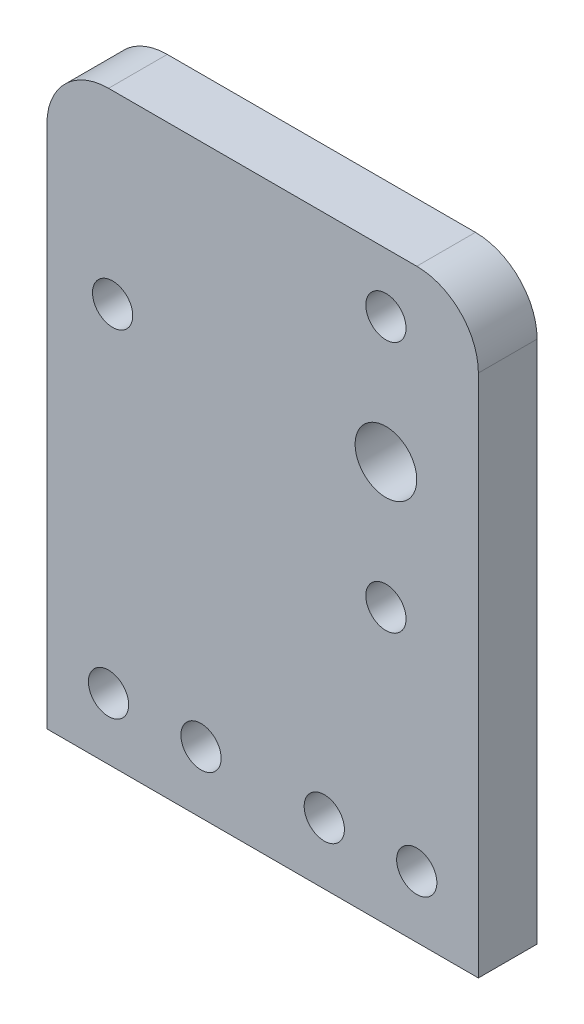
SolidWorks part; units mm, degrees
ref_plane "Front Plane" through (0, 0, 0) normal (0, 0, 1) x (1, 0, 0)
ref_plane "Top Plane" through (0, 0, 0) normal (0, 1, 0) x (1, 0, 0)
ref_plane "Right Plane" through (0, 0, 0) normal (1, 0, 0) x (0, 0, -1)
sketch "Sketch1" plane through (0, 0, 0) normal (0, 0, 1) x (1, 0, 0)
  line L1 (-17.5, 23.75) -> (17.5, 23.75)
  line L2 (-17.5, 23.75) -> (-17.5, -23.75)
  line L3 (-17.5, -23.75) -> (17.5, -23.75)
  line L4 (17.5, 23.75) -> (17.5, -23.75)
  line L5 (-17.5, 23.75) -> (17.5, -23.75) construction
  line L6 (-17.5, -23.75) -> (17.5, 23.75) construction
  circle A0 centre (10, 8.75) radius 2.5
  point P0 (0, 0)
  dimension "D3" = 5
  dimension "D1" = 35
  dimension "D2" = 47.5
  dimension "D4" = 27.5
  dimension "D5" = 32.5
extrude "Boss-Extrude1" add sketch "Sketch1" along normal blind 4.7625
hole_wizard "#4 Clearance Hole1" positions "Sketch2" profile "Sketch3" hole size "#4" standard "ANSI Inch" end condition up to next
sketch "Sketch2" plane through (0, 0, 4.7625) normal (0, 0, 1) x (1, 0, 0)
  circle A1 centre (10, 8.75) radius 2.5 construction
  circle A2 centre (1.28, 8.75) radius 17.57 construction
  point P0 (10, 18.96)
  point P2 (10, -1.46)
  point P4 (-12.17, 8.75)
  dimension "D1" = 35.14
  dimension "D4" = 10.21
  dimension "D5" = 10.21
  dimension "D6" = 22.17
  dimension "D7" = 10.21
  dimension "D2" = 8.72
  dimension "D3" = 8.72
sketch "Sketch3" plane through (10, 18.96, 4.7625) normal (1, 0, 0) x (0, -1, 0)
  line L0 (0, 0) -> (0, 4.7625)
  line L1 (0, 4.7625) -> (1.6319, 4.7625)
  line L2 (1.6319, 4.7625) -> (1.6319, 0)
  line L5 (1.6319, 0) -> (0, 0)
  line L11 (0, -6.35) -> (0, 107.95) construction
  dimension "Thru Hole Dia." = 3.2639
  dimension "Thru Hole Depth" = 4.7625
fillet "Fillet1" radius 5 2 edges at (17.5, 23.75, 2.3813) (-17.5, 23.75, 2.3813)
hole_wizard "#4 Clearance Hole2" positions "Sketch4" profile "Sketch5" hole size "#4" standard "ANSI Inch" end condition up to next
sketch "Sketch4" plane through (0, 0, 4.7625) normal (0, 0, 1) x (1, 0, 0)
  line L0 (-17.5, -23.75) -> (17.5, -23.75) construction
  line L1 (-17.5, 18.75) -> (-17.5, -23.75) construction
  line L2 (17.5, -23.75) -> (17.5, 18.75) construction
  point P0 (-12.5, -18.75)
  point P4 (12.5, -18.75)
  point P18 (-5, -18.75)
  point P20 (5, -18.75)
  dimension "D1" = 5
  dimension "D2" = 5
  dimension "D3" = 5
  dimension "D4" = 7.5
  dimension "D5" = 7.5
sketch "Sketch5" plane through (-12.5, -18.75, 4.7625) normal (1, 0, 0) x (0, -1, 0)
  line L0 (0, 0) -> (0, 4.7625)
  line L1 (0, 4.7625) -> (1.6319, 4.7625)
  line L2 (1.6319, 4.7625) -> (1.6319, 0)
  line L5 (1.6319, 0) -> (0, 0)
  line L11 (0, -6.35) -> (0, 107.95) construction
  dimension "Thru Hole Dia." = 3.2639
  dimension "Thru Hole Depth" = 4.7625
equation "\"D3@Sketch4\"=\"D2@Sketch4\""
equation "\"D5@Sketch2\"=\"D4@Sketch2\""
equation "\"D4@Sketch1\"=\"D1@Sketch1\"-7.5"
equation "\"D7@Sketch2\"=\"D4@Sketch2\""
equation "\"D5@Sketch4\"=\"D4@Sketch4\""
equation "\"D2@Sketch1\"=\"D5@Sketch1\"+15"
equation "\"D1@Boss-Extrude1\"=(3/16)*25.4"
